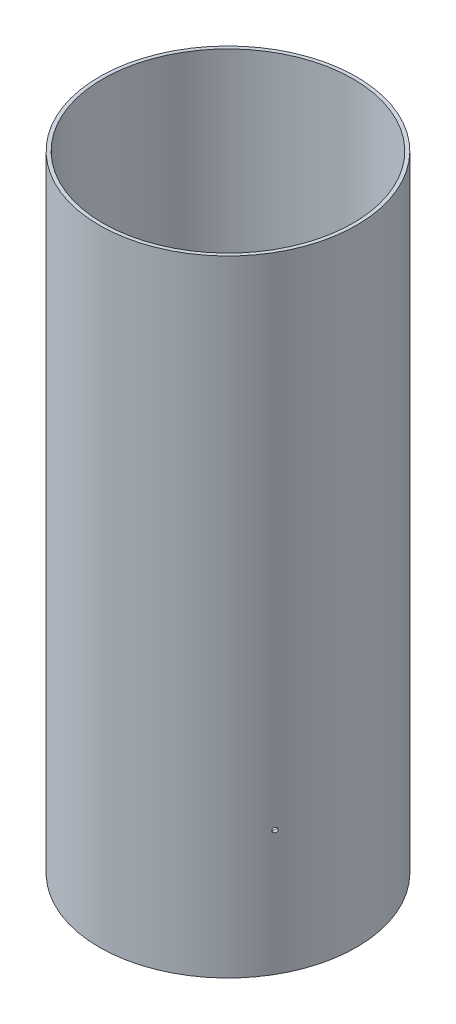
SolidWorks part; units mm, degrees
ref_plane "Front Plane" through (0, 0, 0) normal (0, 0, 1) x (1, 0, 0)
ref_plane "Top Plane" through (0, 0, 0) normal (0, 1, 0) x (1, 0, 0)
ref_plane "Right Plane" through (0, 0, 0) normal (1, 0, 0) x (0, 0, -1)
sketch "Sketch1" plane through (0, 0, 0) normal (0, 1, 0) x (1, 0, 0)
  circle A0 centre (0, 0) radius 76.2
  circle A1 centre (0, 0) radius 78.359
  dimension "D1" = 152.4
  dimension "D2" = 156.718
extrude "Boss-Extrude1" add sketch "Sketch1" along normal blind 381
sketch "Sketch2" plane through (0, 0, 0) normal (0, 0, 1) x (1, 0, 0)
  circle A0 centre (0, 76.2) radius 1.4122
  dimension "D2" = 2.8245
  dimension "D1" = 76.2
extrude "Cut-Extrude1" cut sketch "Sketch2" against normal up to surface (78.3463 mm away)
pattern_circular "CirPattern1" count 3 over 360 about axis through (0, 0, 0) along (0, 1, 0) of "Cut-Extrude1"
